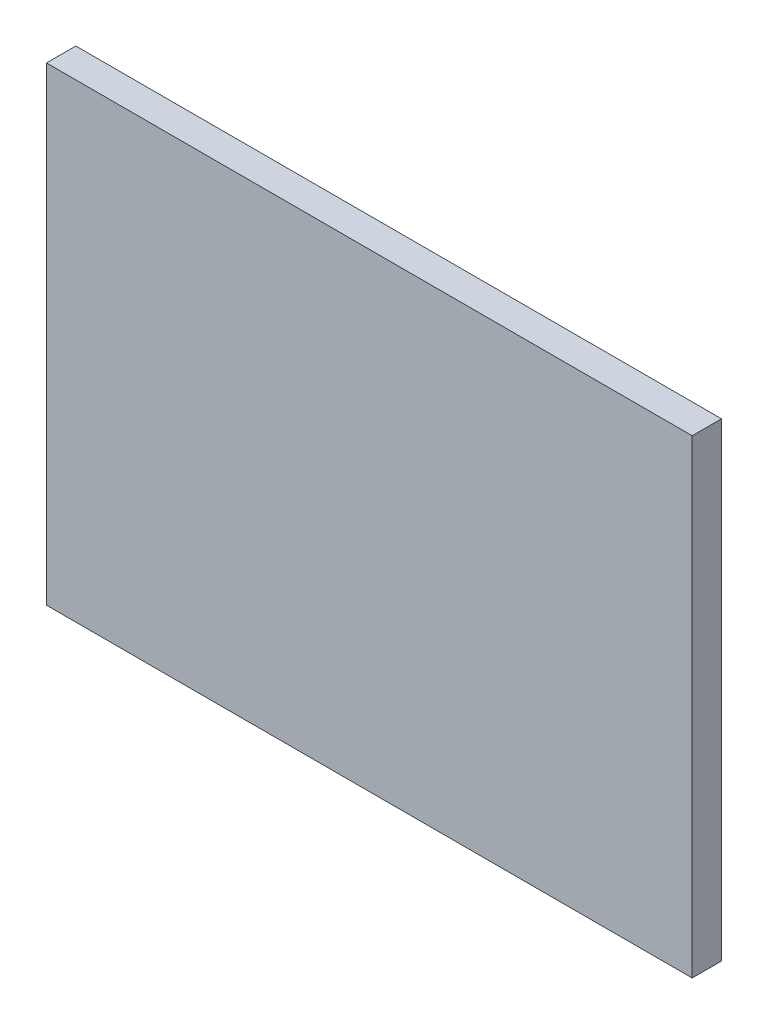
SolidWorks part; units mm, degrees
ref_plane "Front Plane" through (0, 0, 0) normal (0, 0, 1) x (1, 0, 0)
ref_plane "Top Plane" through (0, 0, 0) normal (0, 1, 0) x (1, 0, 0)
ref_plane "Right Plane" through (0, 0, 0) normal (1, 0, 0) x (0, 0, -1)
sketch "Sketch1" plane through (0, 0, 0) normal (0, 0, 1) x (1, 0, 0)
  line L1 (-69.85, -50.8) -> (69.85, -50.8)
  line L2 (-69.85, -50.8) -> (-69.85, 50.8)
  line L3 (-69.85, 50.8) -> (69.85, 50.8)
  line L4 (69.85, -50.8) -> (69.85, 50.8)
  line L5 (-69.85, -50.8) -> (69.85, 50.8) construction
  line L6 (-69.85, 50.8) -> (69.85, -50.8) construction
  point P0 (0, 0)
  point P14 (0, 0)
  dimension "D1" = 139.7
  dimension "D2" = 101.6
extrude "Boss-Extrude1" add sketch "Sketch1" along normal blind 6.35
